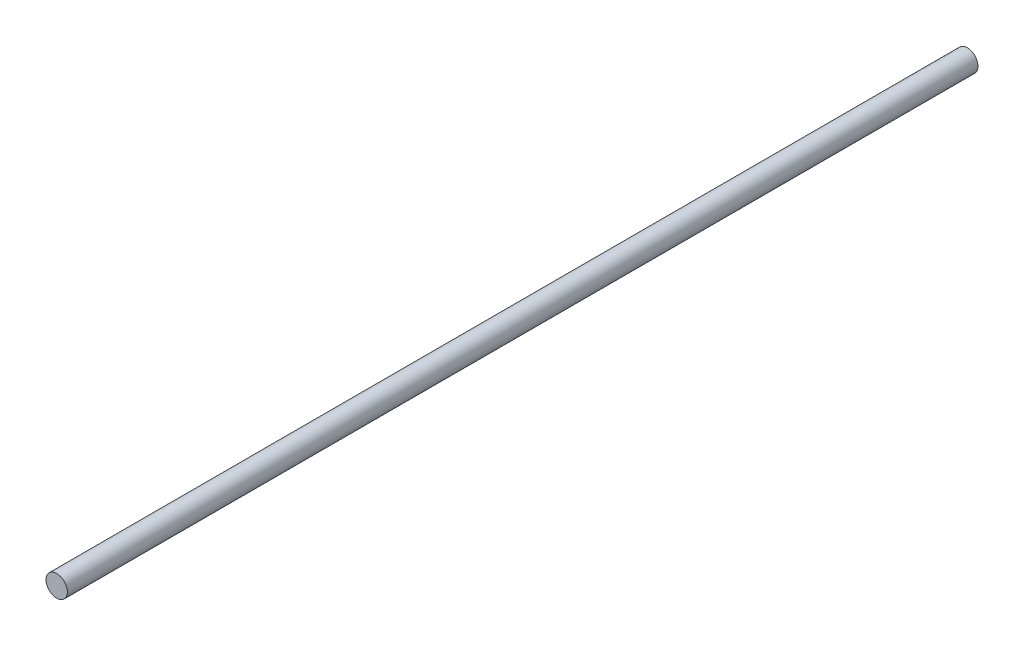
SolidWorks part; units mm, degrees
ref_plane "Спереди" through (0, 0, 0) normal (0, 0, 1) x (1, 0, 0)
ref_plane "Сверху" through (0, 0, 0) normal (0, 1, 0) x (1, 0, 0)
ref_plane "Справа" through (0, 0, 0) normal (1, 0, 0) x (0, 0, -1)
sketch "Эскиз1" plane through (0, 0, 0) normal (0, 0, 1) x (1, 0, 0)
  circle A0 centre (0, 0) radius 6
extrude "Бобышка-Вытянуть1" add sketch "Эскиз1" along normal blind 510
